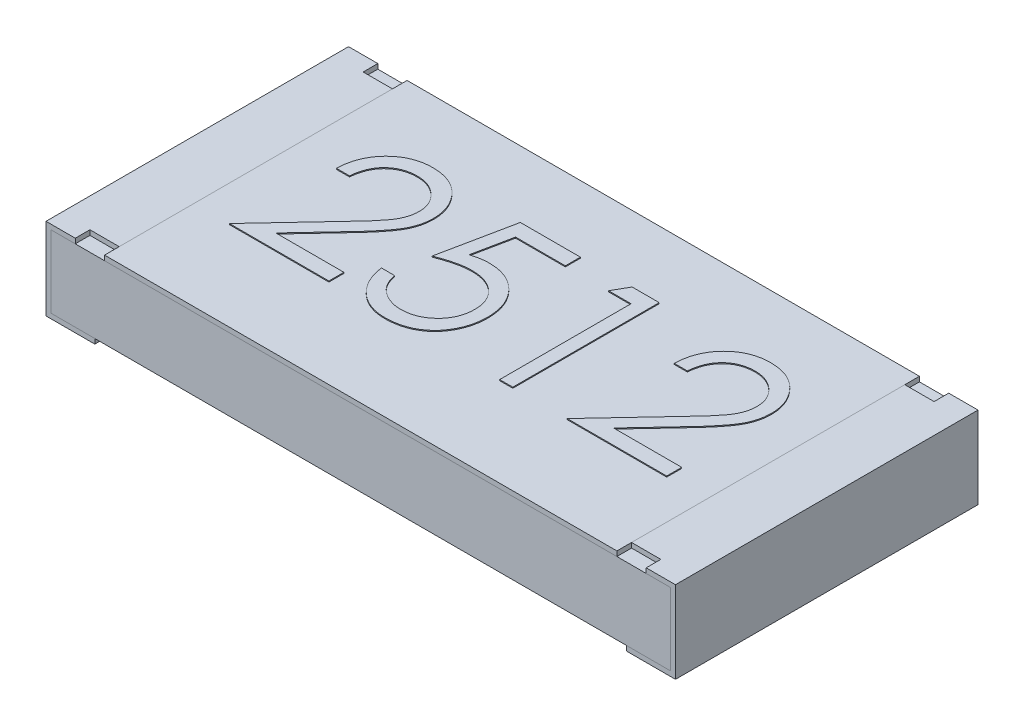
SolidWorks part; units mm, degrees
ref_plane "Alzado" through (0, 0, 0) normal (0, 0, 1) x (1, 0, 0)
ref_plane "Planta" through (0, 0, 0) normal (0, 1, 0) x (1, 0, 0)
ref_plane "Vista lateral" through (0, 0, 0) normal (1, 0, 0) x (0, 0, -1)
sketch "Croquis1" plane through (0, 0, 0) normal (0, 1, 0) x (1, 0, 0)
  line L1 (3.175, 1.55) -> (-3.175, 1.55)
  line L2 (3.175, 1.55) -> (3.175, -1.55)
  line L3 (3.175, -1.55) -> (-3.175, -1.55)
  line L4 (-3.175, 1.55) -> (-3.175, -1.55)
  line L5 (3.175, 1.55) -> (-3.175, -1.55) construction
  line L6 (3.175, -1.55) -> (-3.175, 1.55) construction
  point P0 (0, 0)
  dimension "D1" = 3.1
  dimension "D2" = 6.35
extrude "Extruir1" add sketch "Croquis1" along normal blind 0.79
sketch "Croquis2" plane through (0, 0, 1.55) normal (0, 0, 1) x (1, 0, 0)
  line L0 (3.175, 0.79) -> (3.175, 0) construction
  line L1 (-3.175, 0) -> (3.175, 0)
  line L2 (-3.175, 0) -> (-3.175, 0.05)
  line L3 (-3.175, 0.05) -> (3.175, 0.05)
  line L4 (3.175, 0) -> (3.175, 0.05)
  dimension "D1" = 0.05
extrude "Extruir2" cut sketch "Croquis2" against normal through all
sketch "Croquis3" plane through (0, 0, 1.55) normal (0, 0, 1) x (1, 0, 0)
  line L0 (-2.625, 0.84) -> (-3.225, 0.84)
  line L1 (-3.225, 0.84) -> (-3.225, 0)
  line L2 (-3.225, 0) -> (-2.725, 0)
  line L4 (-3.175, 0.79) -> (-3.175, 0.05) construction
  line L5 (-3.175, 0.79) -> (3.175, 0.79) construction
  dimension "D1" = 0.05
  dimension "D2" = 0.05
  dimension "D3" = 0.6
  dimension "D4" = 0.5
  dimension "D5" = 0.84
sketch3d "Croquis3D1"
  line L0 (-2.625, 0.84, 1.55) -> (-2.625, 0.84, -1.55)
  line L1 (-2.625, 0.84, -1.55) -> (-2.625, 0.79, -1.55)
  line L2 (-2.625, 0.79, -1.55) -> (-2.625, 0.79, 1.55)
  line L3 (-2.625, 0.79, 1.55) -> (-2.625, 0.84, 1.55)
  line L4 (-3.175, 0.79, -1.55) -> (-3.175, 0.79, 1.55) construction
sweep "Barrer1" add profiles "Croquis3D1" path "Croquis3"
ref_plane "Plano1" through (0, 0.79, 1.55) normal (1, 0, 0) x (0, 0, -1)
mirror "Simetría1" about plane through (0, 0.79, 1.55) normal (1, 0, 0) of bodies 104
sketch "Croquis4" plane through (-2.625, 0, 0) normal (1, 0, 0) x (0, 0, -1)
  line L1 (-1.55, 0.84) -> (1.55, 0.84)
  line L2 (-1.55, 0.84) -> (-1.55, 0.79)
  line L3 (-1.55, 0.79) -> (1.55, 0.79)
  line L4 (1.55, 0.84) -> (1.55, 0.79)
extrude "Extruir3" add sketch "Croquis4" along normal up to surface (5.25 mm away) separate body up to face at (2.625, 0.815, 0)
sketch "Croquis5" plane through (0, 0.84, 0) normal (0, 1, 0) x (1, 0, 0)
  line L0 (0, -1.55) -> (0, 1.55) construction
  line L1 (-2.625, -1.55) -> (-2.925, -1.55)
  line L2 (-2.625, -1.55) -> (-2.625, -1.4)
  line L3 (-2.625, -1.4) -> (-2.925, -1.4)
  line L4 (-2.925, -1.55) -> (-2.925, -1.4)
  line L5 (2.625, -1.55) -> (-2.625, -1.55) construction
  line L6 (2.625, 1.55) -> (-2.625, 1.55) construction
  line L7 (-2.625, 0) -> (2.625, 0) construction
  line L8 (-2.625, 1.55) -> (-2.625, -1.55) construction
  line L9 (2.625, 1.55) -> (2.625, -1.55) construction
  line L10 (-2.925, 1.55) -> (-2.925, 1.4)
  line L11 (-2.625, 1.4) -> (-2.925, 1.4)
  line L12 (-2.625, 1.55) -> (-2.625, 1.4)
  line L13 (-2.625, 1.55) -> (-2.925, 1.55)
  line L14 (2.625, 1.55) -> (2.925, 1.55)
  line L15 (2.625, 1.55) -> (2.625, 1.4)
  line L16 (2.625, 1.4) -> (2.925, 1.4)
  line L17 (2.925, 1.55) -> (2.925, 1.4)
  line L18 (2.925, -1.55) -> (2.925, -1.4)
  line L19 (2.625, -1.4) -> (2.925, -1.4)
  line L20 (2.625, -1.55) -> (2.625, -1.4)
  line L21 (2.625, -1.55) -> (2.925, -1.55)
  dimension "D1" = 0.15
  dimension "D2" = 0.3
extrude "Extruir4" cut sketch "Croquis5" against normal up to next (0.05 mm away)
sketch "Sketch1" plane through (0, 0.84, 0) normal (0, 1, 0) x (1, 0, 0)
  text T0 "2512" font "Century Gothic" height 1.5
extrude "Boss-Extrude1" add sketch "Sketch1" along normal blind 0.01
